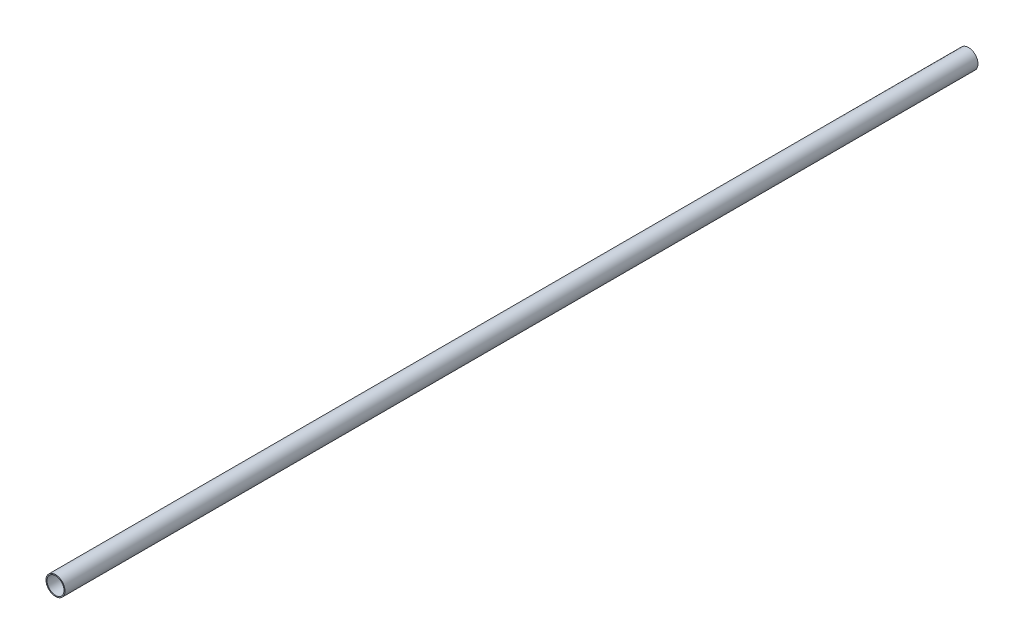
SolidWorks part; units mm, degrees
ref_plane "Front" through (0, 0, 0) normal (0, 0, 1) x (1, 0, 0)
ref_plane "Top" through (0, 0, 0) normal (0, 1, 0) x (1, 0, 0)
ref_plane "Side" through (0, 0, 0) normal (1, 0, 0) x (0, 0, -1)
other "Configuration Table"
sketch "PipeSketch" plane through (0, 0, 0) normal (0, 0, 1) x (1, 0, 0)
  circle A0 centre (0, 0) radius 57.15
  circle A1 centre (0, 0) radius 51.1302
  dimension "OuterDiameter" = 114.3
  dimension "InnerDiameter" = 102.2604
extrude "Extrusion" add sketch "PipeSketch" along normal blind 5486.4
sketch "FilterSketch" plane through (0, 0, 0) normal (0, 0, 1) x (1, 0, 0)
  circle A0 centre (0, 0) radius 50.8 construction
  dimension "NominalDiameter" = 101.6
